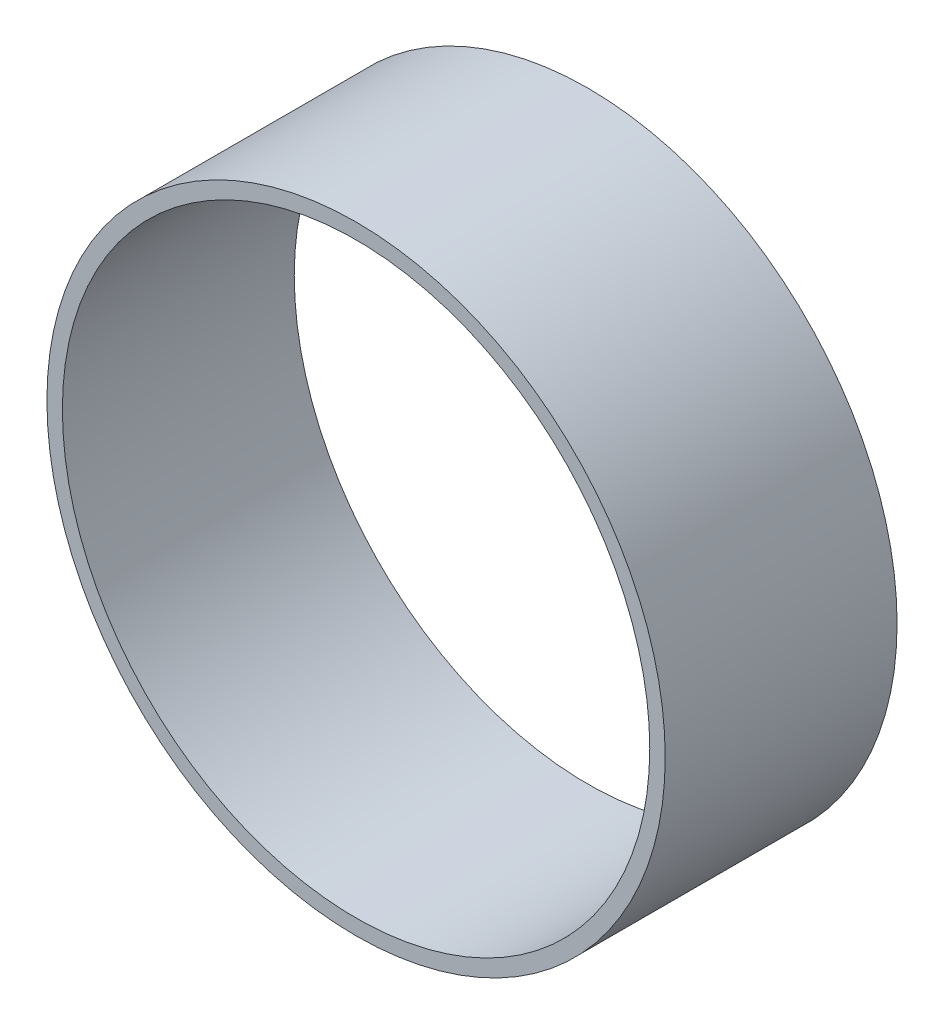
SolidWorks part; units mm, degrees
ref_plane "前视基准面" through (0, 0, 0) normal (0, 0, 1) x (1, 0, 0)
ref_plane "上视基准面" through (0, 0, 0) normal (0, 1, 0) x (1, 0, 0)
ref_plane "右视基准面" through (0, 0, 0) normal (1, 0, 0) x (0, 0, -1)
sketch "草图1" plane through (0, 0, 0) normal (0, 0, 1) x (1, 0, 0)
  circle A0 centre (0, 0) radius 38
  circle A1 centre (0, 0) radius 40
extrude "凸台-拉伸1" add sketch "草图1" along normal blind 30
